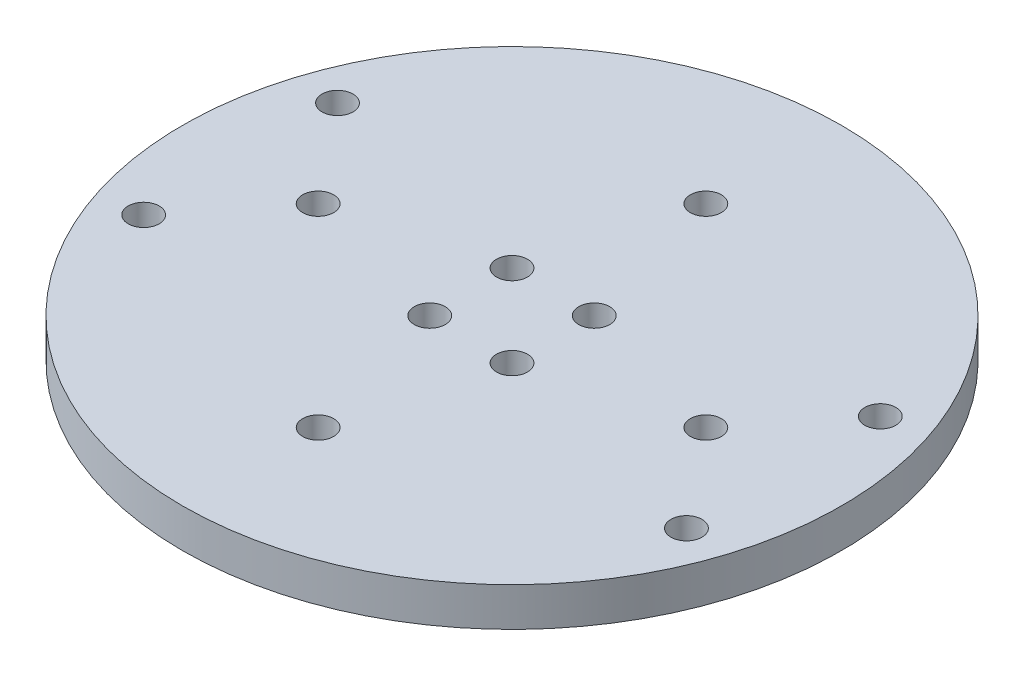
SolidWorks part; units mm, degrees
material "ﾎﾟﾘ塩化ﾋﾞﾆﾙ(PVC)硬質"
ref_plane "正面" through (0, 0, 0) normal (0, 0, 1) x (1, 0, 0)
ref_plane "平面" through (0, 0, 0) normal (0, 1, 0) x (1, 0, 0)
ref_plane "右側面" through (0, 0, 0) normal (1, 0, 0) x (0, 0, -1)
sketch "ｽｹｯﾁ1" plane through (0, 0, 0) normal (0, 1, 0) x (1, 0, 0)
  line L1 (-5.3033, 5.3033) -> (5.3033, 5.3033) construction
  line L2 (-5.3033, 5.3033) -> (-5.3033, -5.3033) construction
  line L3 (-5.3033, -5.3033) -> (5.3033, -5.3033) construction
  line L4 (5.3033, 5.3033) -> (5.3033, -5.3033) construction
  line L5 (-5.3033, 5.3033) -> (5.3033, -5.3033) construction
  line L6 (-5.3033, -5.3033) -> (5.3033, 5.3033) construction
  line L7 (-35, -12.5) -> (35, -12.5) construction
  line L8 (-35, -12.5) -> (-35, 12.5) construction
  line L9 (-35, 12.5) -> (35, 12.5) construction
  line L10 (35, -12.5) -> (35, 12.5) construction
  line L11 (-35, -12.5) -> (35, 12.5) construction
  line L12 (-35, 12.5) -> (35, -12.5) construction
  circle A0 centre (0, 0) radius 42.5
  circle A1 centre (5.3033, 5.3033) radius 2
  circle A2 centre (5.3033, -5.3033) radius 2
  circle A3 centre (-5.3033, -5.3033) radius 2
  circle A4 centre (-5.3033, 5.3033) radius 2
  circle A5 centre (0, 0) radius 25 construction
  circle A6 centre (25, 0) radius 2
  circle A7 centre (0, -25) radius 2
  circle A8 centre (-25, 0) radius 2
  circle A9 centre (0, 25) radius 2
  circle A10 centre (35, 12.5) radius 2
  circle A11 centre (35, -12.5) radius 2
  circle A12 centre (-35, -12.5) radius 2
  circle A13 centre (-35, 12.5) radius 2
  point P17 (0, 0)
  point P26 (0, 0)
  dimension "D1" = 85
  dimension "D3" = 4
  dimension "D5" = 50
  dimension "D6" = 4
  dimension "D10" = 4
  dimension "D2" = 15
  dimension "D8" = 70
  dimension "D9" = 25
  dimension "D4" = 4
  dimension "D7" = 4
extrude "ﾎﾞｽ - 押し出し1" add sketch "ｽｹｯﾁ1" along normal blind 5
